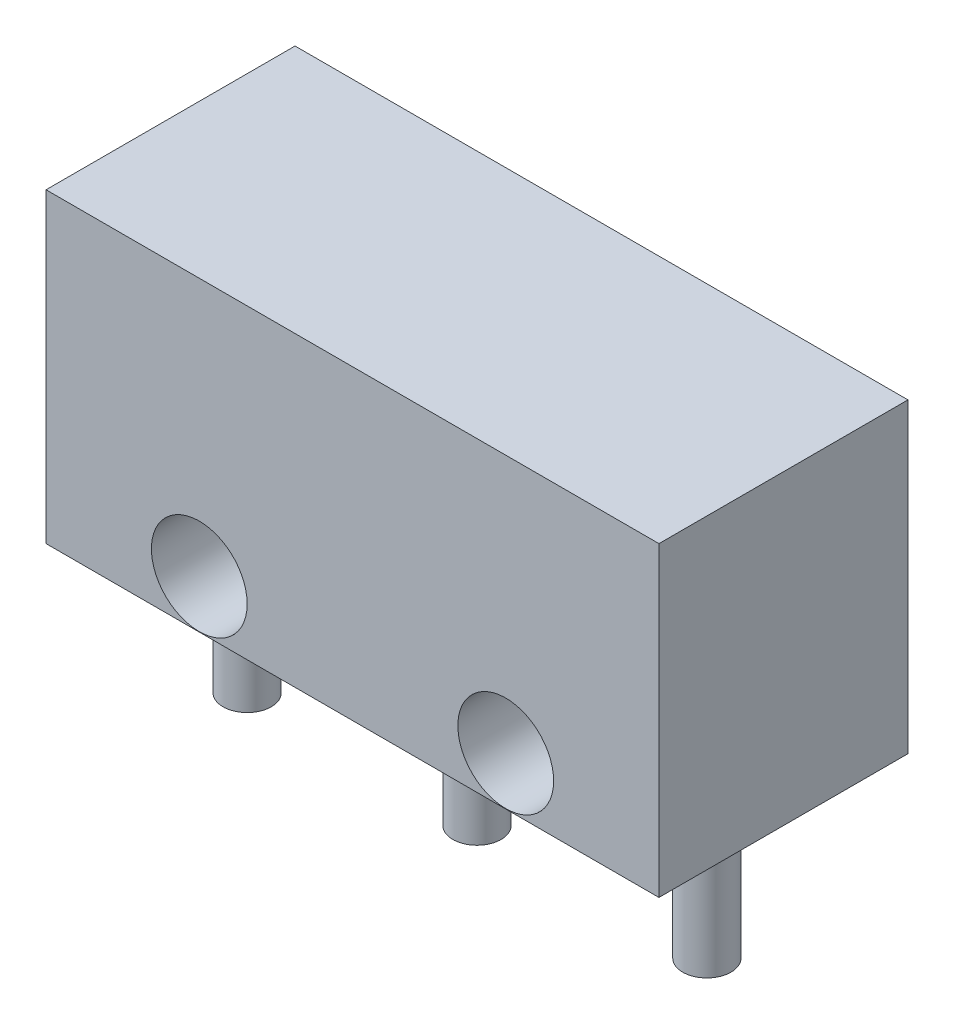
SolidWorks part; units mm, degrees
ref_plane "Front Plane" through (0, 0, 0) normal (0, 0, 1) x (1, 0, 0)
ref_plane "Top Plane" through (0, 0, 0) normal (0, 1, 0) x (1, 0, 0)
ref_plane "Right Plane" through (0, 0, 0) normal (1, 0, 0) x (0, 0, -1)
sketch "Sketch1" plane through (0, 0, 0) normal (0, 1, 0) x (1, 0, 0)
  line L1 (0, 0) -> (12.7, 0)
  line L2 (0, 0) -> (0, 5.1594)
  line L3 (0, 5.1594) -> (12.7, 5.1594)
  line L4 (12.7, 0) -> (12.7, 5.1594)
  dimension "D1" = 12.7
  dimension "D2" = 5.1594
extrude "Boss-Extrude1" add sketch "Sketch1" along normal blind 6.35
sketch "Sketch2" plane through (0, 0, 0) normal (0, -1, 0) x (1, 0, 0)
  line L0 (0, 0) -> (12.7, 0) construction
  line L2 (0, -5.1594) -> (0, 0) construction
  circle A0 centre (6.35, -2.5797) radius 0.5
  circle A1 centre (1.5875, -2.5797) radius 0.5
  circle A2 centre (11.1125, -2.5797) radius 0.5
  point P8 (0, 0)
  point P13 (8.3685, -2.5195)
  dimension "D4" = 1
  dimension "D5" = 1
  dimension "D6" = 1
  dimension "D8" = 4.7625
  dimension "D9" = 4.7625
  dimension "D1" = 2.5797
  dimension "D2" = 2.5797
  dimension "D3" = 2.5797
  dimension "D7" = 6.35
extrude "Boss-Extrude2" add sketch "Sketch2" along normal blind 3.175
sketch "Sketch3" plane through (0, 0, 0) normal (0, 0, 1) x (1, 0, 0)
  line L0 (0, 0) -> (12.7, 0) construction
  line L2 (0, 6.35) -> (0, 0) construction
  circle A0 centre (9.525, 1) radius 0.9922
  circle A1 centre (3.175, 1) radius 0.9922
  dimension "D1" = 1.9844
  dimension "D2" = 1.9844
  dimension "D3" = 6.35
  dimension "D4" = 1
  dimension "D5" = 1
  dimension "D6" = 3.175
extrude "Cut-Extrude1" cut sketch "Sketch3" against normal through all
